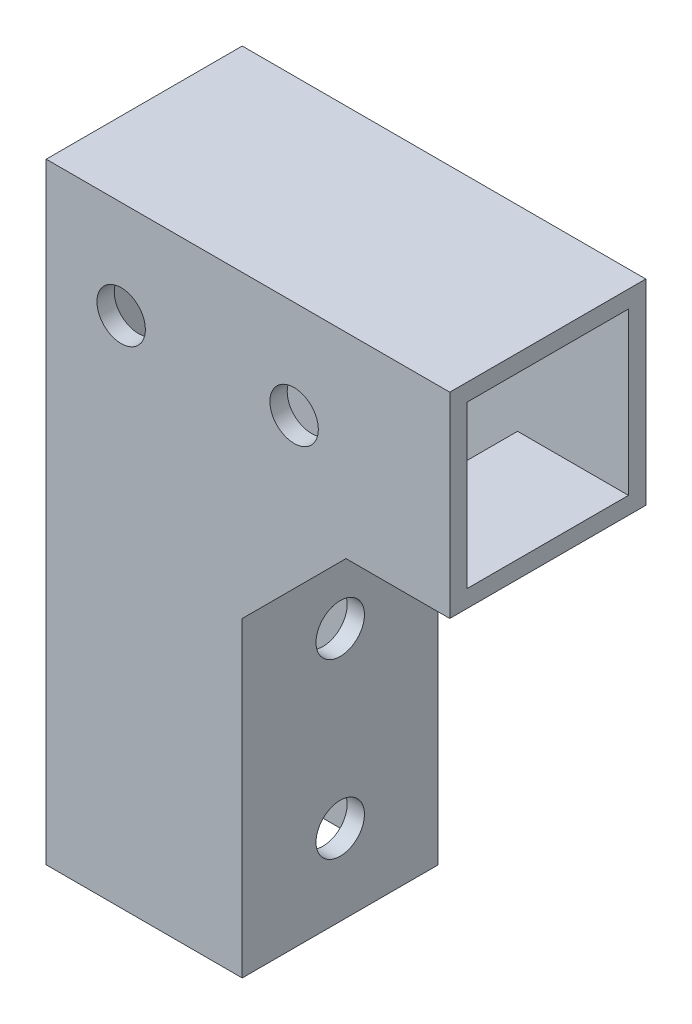
SolidWorks part; units mm, degrees
ref_plane "Front Plane" through (0, 0, 0) normal (0, 0, 1) x (1, 0, 0)
ref_plane "Top Plane" through (0, 0, 0) normal (0, 1, 0) x (1, 0, 0)
ref_plane "Right Plane" through (0, 0, 0) normal (1, 0, 0) x (0, 0, -1)
sketch "Sketch1" plane through (0, 0, 0) normal (0, 0, 1) x (1, 0, 0)
  line L1 (0, 0) -> (17, 0)
  line L2 (0, 0) -> (0, 53)
  line L5 (0, 53) -> (35, 53)
  line L8 (35, 53) -> (35, 36)
  line L9 (26, 36) -> (35, 36)
  line L10 (17, 27) -> (17, 0)
  line L11 (17, 27) -> (26, 36)
  dimension "D1" = 17
  dimension "D2" = 27
  dimension "D3" = 35
  dimension "D4" = 9
  dimension "D5" = 9
extrude "Shape" add sketch "Sketch1" along normal blind 17
sketch "Sketch2" plane through (0, 0, 0) normal (0, 1, 0) x (1, 0, 0)
  line L0 (0, -17) -> (17, -17) construction
  line L1 (1.5, -15.5) -> (15.5, -15.5)
  line L2 (1.5, -15.5) -> (1.5, -1.5)
  line L3 (1.5, -1.5) -> (15.5, -1.5)
  line L4 (15.5, -15.5) -> (15.5, -1.5)
  line L6 (0, -17) -> (0, 0) construction
  dimension "D1" = 14
  dimension "D2" = 1.5
  dimension "D3" = 1.5
extrude "Thrust Load Cell Slot" cut sketch "Sketch2" along normal blind 51.5
ref_plane "Chamfer Hollowing Plane" through (0, 0, 1.5) normal (0, 0, 1) x (1, 0, 0)
sketch "Sketch6" plane through (0, 0, 1.5) normal (0, 0, 1) x (1, 0, 0)
  line L0 (25.3787, 37.5) -> (15.5, 27.6213)
  line L1 (15.5, 27.6213) -> (15.5, 37.5)
  line L2 (15.5, 37.5) -> (25.3787, 37.5)
  line L3 (17, 0) -> (17, 27) construction
  line L4 (26, 36) -> (35, 36) construction
  line L5 (17, 27) -> (26, 36) construction
  dimension "D1" = 1.5
  dimension "D2" = 1.5
  dimension "D3" = 1.5
extrude "Chamfer Hollowing" cut sketch "Sketch6" along normal blind 14
sketch "Sketch3" plane through (0, 0, 0) normal (1, 0, 0) x (0, 0, -1)
  line L0 (0, 27) -> (-17, 27) construction
  line L4 (0, 53) -> (0, 0) construction
  line L5 (-17, 53) -> (-17, 0) construction
  line L6 (-17, 0) -> (0, 0) construction
  circle A0 centre (-8.5, 22) radius 2.1
  circle A1 centre (-8.5, 7) radius 2.1
  dimension "D2" = 4.2
  dimension "D1" = 27
  dimension "D3" = 5
  dimension "D4" = 15
  dimension "D5" = 8.5
extrude "Thrust Load Cell Holes" cut sketch "Sketch3" along normal through all
ref_plane "Torque Load Cell Plane" through (35, 0, 0) normal (1, 0, 0) x (0, 0, -1)
sketch "Sketch4" plane through (35, 0, 0) normal (1, 0, 0) x (0, 0, -1)
  line L0 (-17, 53) -> (0, 53) construction
  line L1 (-15.5, 51.5) -> (-1.5, 51.5)
  line L2 (-15.5, 51.5) -> (-15.5, 37.5)
  line L3 (-15.5, 37.5) -> (-1.5, 37.5)
  line L4 (-1.5, 51.5) -> (-1.5, 37.5)
  line L5 (0, 36) -> (0, 53) construction
  dimension "D1" = 14
  dimension "D2" = 1.5
  dimension "D3" = 1.5
extrude "Torque Load Cell Slot" cut sketch "Sketch4" against normal blind 27
sketch "Sketch7" plane through (0, 0, 0) normal (0, 0, 1) x (1, 0, 0)
  line L0 (1.5, 53) -> (1.5, 0) construction
  line L1 (35, 53) -> (0, 53) construction
  line L2 (0, 0) -> (17, 0) construction
  line L3 (0, 53) -> (0, 0) construction
  line L4 (0, 51.5) -> (35, 51.5) construction
  line L5 (35, 36) -> (35, 53) construction
  circle A0 centre (6.5, 44.5) radius 2.1
  circle A1 centre (21.5, 44.5) radius 2.1
  dimension "D4" = 4.2
  dimension "D1" = 1.5
  dimension "D2" = 5
  dimension "D3" = 15
  dimension "D5" = 1.5
  dimension "D6" = 7
extrude "Torque Load Cell Holes" cut sketch "Sketch7" along normal through all
sketch "Sketch8" plane through (0, 0, 0) normal (1, 0, 0) x (0, 0, -1)
  line L1 (-6, 49) -> (-11, 49)
  line L2 (-6, 49) -> (-6, 33)
  line L3 (-6, 33) -> (-11, 33)
  line L4 (-11, 49) -> (-11, 33)
  line L5 (-17, 53) -> (0, 53) construction
  line L6 (-8.5, 53) -> (-8.5, 0) construction
  line L7 (-17, 0) -> (0, 0) construction
  dimension "D1" = 5
  dimension "D2" = 2.5
  dimension "D3" = 16
  dimension "D4" = 4
extrude "Boss-Extrude2" add sketch "Sketch8" against normal blind 2
ref_plane "Plane1" through (0, 49, 0) normal (0, 1, 0) x (1, 0, 0)
sketch "Sketch9" plane through (0, 49, 0) normal (0, 1, 0) x (1, 0, 0)
  line L0 (-2, -6) -> (-2, -11) construction
  line L1 (-2, -7.95) -> (-1.1, -7.95)
  line L2 (-2, -7.95) -> (-2, -9.05)
  line L3 (-2, -9.05) -> (-1.1, -9.05)
  line L5 (0, -6) -> (0, -11) construction
  line L6 (-2, -8.5) -> (0, -8.5) construction
  line L7 (-1.1, -6.9) -> (0, -6.9)
  line L8 (-1.1, -6.9) -> (-1.1, -7.95)
  line L9 (-1.1, -10.1) -> (0, -10.1)
  line L10 (0, -6.9) -> (0, -10.1)
  line L11 (-2, -11) -> (0, -11) construction
  line L12 (-2, -6) -> (0, -6) construction
  line L13 (-1.1, -9.05) -> (-1.1, -10.1)
  dimension "D1" = 1.1
  dimension "D2" = 0.55
  dimension "D3" = 0.9
  dimension "D4" = 0.9
  dimension "D5" = 1.1
extrude "Cut-Extrude1" cut sketch "Sketch9" against normal blind 15
